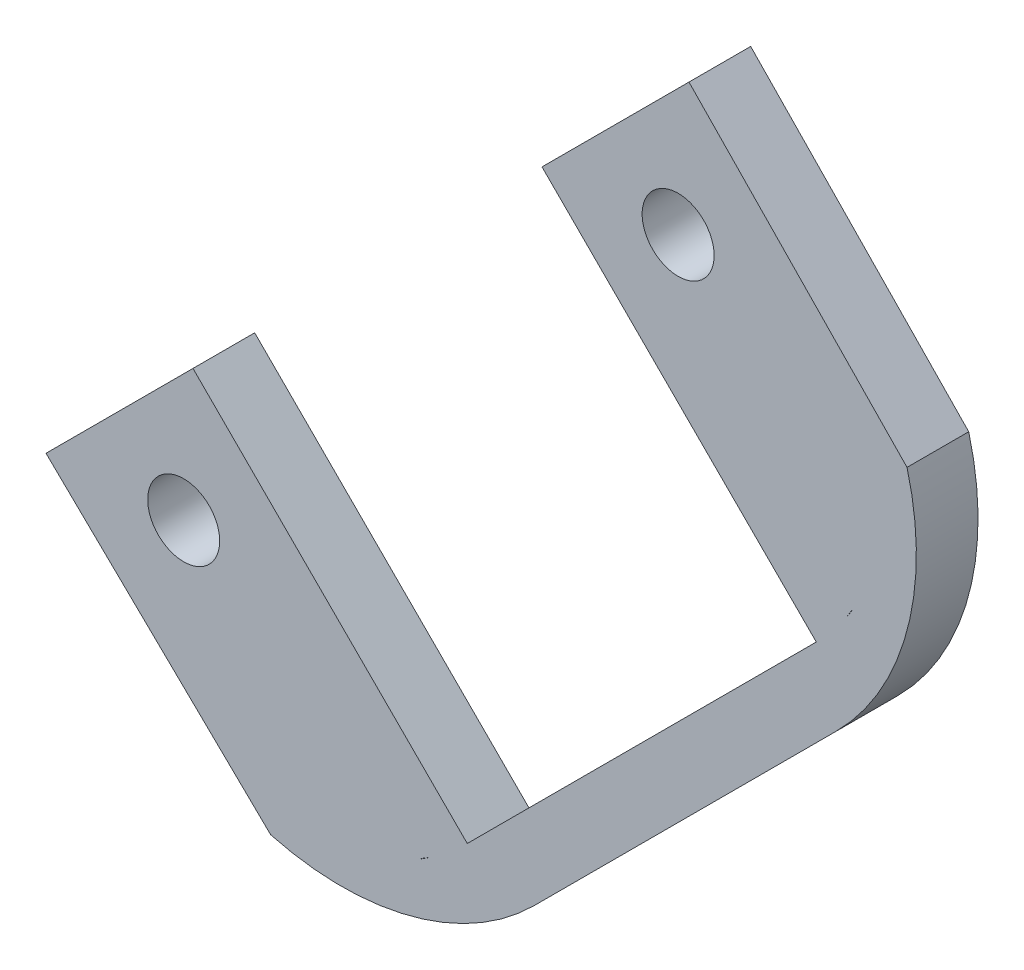
SolidWorks part; units mm, degrees
ref_plane "Front Plane" through (0, 0, 0) normal (0, 0, 1) x (1, 0, 0)
ref_plane "Top Plane" through (0, 0, 0) normal (0, 1, 0) x (1, 0, 0)
ref_plane "Right Plane" through (0, 0, 0) normal (1, 0, 0) x (0, 0, -1)
sketch "Sketch1" plane through (0, 0, 0) normal (0, 0, 1) x (1, 0, 0)
  line L0 (-78.685, 61.7144) -> (-61.5183, 44.5477)
  line L1 (-61.5183, 44.5477) -> (-44.5477, 61.5183)
  line L2 (-44.5477, 61.5183) -> (-61.7144, 78.685)
  line L3 (-58.255, 43.5684) -> (-43.5684, 58.255)
  line L4 (-53.033, 53.033) -> (-50.9117, 50.9117)
  arc A0 (-58.255, 43.5684) -> (-75.4855, 42.2516) centre (-67.6376, 52.9509) cw
  arc A2 (-61.5183, 44.5477) -> (-78.685, 61.7144) centre (-70.1016, 53.1311) cw
  arc A3 (-61.7144, 78.685) -> (-44.5477, 61.5183) centre (-53.1311, 70.1016) cw
  circle A4 centre (-51.2652, 75.3069) radius 1.75
  circle A5 centre (-75.3069, 51.2652) radius 1.75
  arc A6 (-43.1444, 60.4573) -> (-42.7452, 63.8182) centre (-40.0316, 61.7918) cw
  arc A7 (-60.4573, 43.1444) -> (-63.8182, 42.7452) centre (-61.7918, 40.0316) ccw
  arc A8 (-60.4573, 43.1444) -> (-58.255, 43.5684) centre (-59.6692, 44.9826) ccw
  arc A9 (-43.1444, 60.4573) -> (-43.5684, 58.255) centre (-44.9826, 59.6692) cw
  arc A10 (-43.5684, 58.255) -> (-42.2516, 75.4855) centre (-52.9509, 67.6376) ccw
  dimension "D1" = 2
extrude "Boss-Extrude2" add sketch "Sketch1" along normal blind 3 contours A7 A2 L0 A5 | A8 A7 A2 A0 | A7 A8 L3 L4 L1 A2 | A9 A6 A3 L1 L4 L3 | A9 A10 A3 A6 | A3 A6 L2 A4
sketch "Sketch2" plane through (0, 0, 3) normal (0, 0, 1) x (1, 0, 0)
  line L0 (-82.0022, 50.7382) -> (-71.0779, 40.1358)
  line L1 (-53.033, 53.033) -> (-64.1498, 64.1498)
  line L2 (-61.5183, 44.5477) -> (-44.5477, 61.5183) construction
  line L3 (-50.7382, 82.0022) -> (-40.1358, 71.0779)
  line L4 (-71.0779, 40.1358) -> (-82.0022, 40.1358)
  line L5 (-71.0779, 40.1358) -> (-71.0779, 50.7382)
  line L6 (-71.0779, 50.7382) -> (-82.0022, 50.7382)
  line L7 (-82.0022, 40.1358) -> (-82.0022, 50.7382)
  line L8 (-50.7382, 71.0779) -> (-50.7382, 82.0022)
  line L9 (-40.1358, 82.0022) -> (-50.7382, 82.0022)
  line L10 (-40.1358, 71.0779) -> (-40.1358, 82.0022)
  line L11 (-40.1358, 71.0779) -> (-50.7382, 71.0779)
  line L12 (-82.0022, 50.7382) -> (-73.5955, 59.1449)
  line L13 (-73.5955, 59.1449) -> (-82.0022, 67.5515)
  line L14 (-82.0022, 67.5515) -> (-87.146, 55.8821)
  line L15 (-87.146, 55.8821) -> (-82.0022, 50.7382)
  line L16 (-55.8821, 87.146) -> (-50.7382, 82.0022)
  line L17 (-67.5515, 82.0022) -> (-55.8821, 87.146)
  line L18 (-59.1449, 73.5955) -> (-67.5515, 82.0022)
  line L19 (-50.7382, 82.0022) -> (-59.1449, 73.5955)
  arc A0 (-78.685, 61.7144) -> (-75.4855, 42.2516) centre (-70.1016, 53.1311) ccw construction
  arc A1 (-75.4855, 42.2516) -> (-58.255, 43.5684) centre (-67.6376, 52.9509) ccw construction
  arc M14 (-43.5684, 58.255) -> (-42.2516, 75.4855) centre (-52.9509, 67.6376) ccw
  arc M15 (-42.2516, 75.4855) -> (-61.7144, 78.685) centre (-53.1311, 70.1016) ccw
  line M16 (-61.7144, 78.685) -> (-44.5477, 61.5183)
  line M18 (-61.5183, 44.5477) -> (-78.685, 61.7144)
  arc M19 (-78.685, 61.7144) -> (-75.4855, 42.2516) centre (-70.1016, 53.1311) ccw
  arc M20 (-75.4855, 42.2516) -> (-58.255, 43.5684) centre (-67.6376, 52.9509) ccw
extrude "Cut-Extrude5" cut sketch "Sketch2" against normal through all contours L14 L15 L12 L13 M19 M18 | L12 M19 M18 | L0 M19 M20 | L7 L4 M20 M19 | L19 L16 L17 L18 M16 M15 | L19 M15 M16 | L3 M15 M14 | L10 L9 M14 M15
